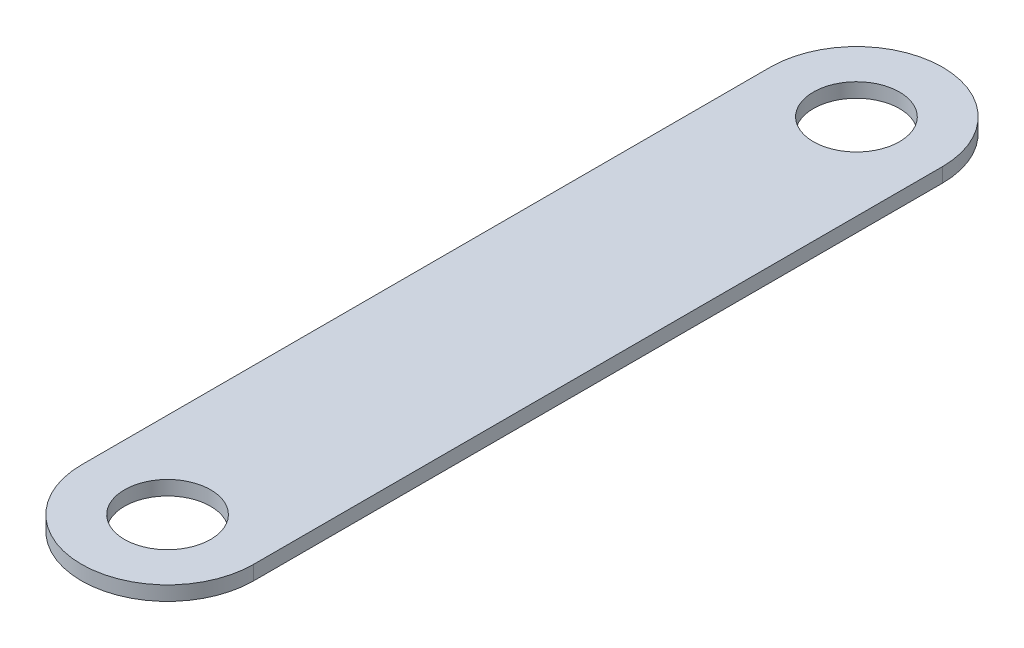
SolidWorks part; units mm, degrees
ref_plane "Front Plane" through (0, 0, 0) normal (0, 0, 1) x (1, 0, 0)
ref_plane "Top Plane" through (0, 0, 0) normal (0, 1, 0) x (1, 0, 0)
ref_plane "Right Plane" through (0, 0, 0) normal (1, 0, 0) x (0, 0, -1)
sketch "Sketch1" plane through (0, 0, 0) normal (0, 1, 0) x (1, 0, 0)
  line L0 (-38.1, 0) -> (-38.1, -304.8)
  line L1 (38.1, 0) -> (38.1, -304.8)
  arc A0 (38.1, 0) -> (-38.1, 0) centre (0, 0) ccw
  arc A1 (-38.1, -304.8) -> (38.1, -304.8) centre (0, -304.8) ccw
  circle A2 centre (0, 0) radius 19.05
  circle A3 centre (0, -304.8) radius 19.05
  dimension "D1" = 76.2
  dimension "D2" = 76.2
  dimension "D4" = 38.1
  dimension "D5" = 38.1
  dimension "D3" = 304.8
extrude "Boss-Extrude1" add sketch "Sketch1" along normal blind 6.35 contours A0 L0 A1 L1
